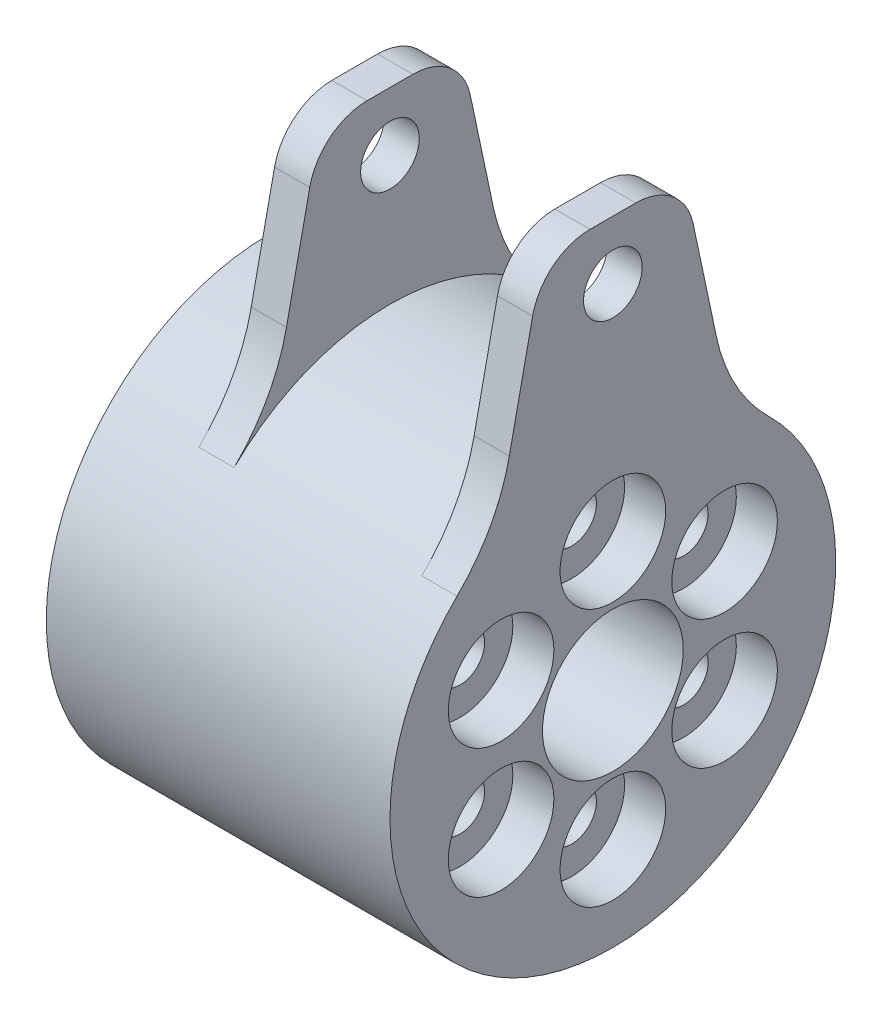
SolidWorks part; units mm, degrees
material "1023 碳钢板 (SS)"
ref_plane "前视基准面" through (0, 0, 0) normal (0, 0, 1) x (1, 0, 0)
ref_plane "上视基准面" through (0, 0, 0) normal (0, 1, 0) x (1, 0, 0)
ref_plane "右视基准面" through (0, 0, 0) normal (1, 0, 0) x (0, 0, -1)
sketch "草图1" plane through (0, 0, 0) normal (1, 0, 0) x (0, 0, -1)
  circle A0 centre (0, 0) radius 19
  circle A1 centre (0, -15) radius 2
  circle A2 centre (0, 13.5) radius 2
  circle A3 centre (11.6913, -6.75) radius 2
  circle A4 centre (-12.9904, 7.5) radius 2
  circle A5 centre (-11.6913, -6.75) radius 2
  circle A6 centre (12.9904, 7.5) radius 2
  circle A7 centre (0, 0) radius 11
  point P17 (0, 0)
  dimension "D1" = 38
  dimension "D2" = 4
  dimension "D3" = 4
  dimension "D4" = 13.5
  dimension "D5" = 15
  dimension "D7" = 22
  dimension "D6" = 3
extrude "凸台-拉伸1" add sketch "草图1" along normal blind 3
sketch "草图3" plane through (3, 0, 0) normal (1, 0, 0) x (0, 0, -1)
  arc A0 (-2.7954, 10.6389) -> (2.7954, 10.6389) centre (0, 13.5) ccw
  circle A1 centre (0, 0) radius 11 construction
  arc A2 (2.7954, 10.6389) -> (-2.7954, 10.6389) centre (0, 0) ccw
  arc A3 (10.6112, -2.8986) -> (7.8159, -7.7403) centre (11.6913, -6.75) ccw
  arc A4 (7.8159, -7.7403) -> (10.6112, -2.8986) centre (0, 0) ccw
  arc A5 (-7.8159, -7.7403) -> (-10.6112, -2.8986) centre (-11.6913, -6.75) ccw
  arc A6 (-10.6112, -2.8986) -> (-7.8159, -7.7403) centre (0, 0) ccw
  circle A7 centre (0, 13.5) radius 2 construction
  point P14 (0, 0)
  dimension "D1" = 8
  dimension "D2" = 3
extrude "凸台-拉伸2" add sketch "草图3" against normal up to surface (3 mm away) up to face at (0, 0, -19)
fillet "圆角1" radius 3 6 edges at (1.5, 10.6389, -2.7954) (1.5, 10.6389, 2.7954) (1.5, -7.7403, -7.8159) (1.5, -2.8986, -10.6112) (1.5, -2.8986, 10.6112) (1.5, -7.7403, 7.8159)
sketch "草图5" plane through (3, 0, 0) normal (1, 0, 0) x (0, 0, -1)
  line L0 (0, 0) -> (0, 54.073) construction
  line L1 (-6, 35) -> (-10, 16.1555)
  line L2 (6, 35) -> (10, 16.1555)
  line L3 (-6, 35) -> (6, 35)
  circle A0 centre (0, 30) radius 2.5
  circle A2 centre (0, 0) radius 19 construction
  arc A3 (10, 16.1555) -> (-10, 16.1555) centre (0, 0) ccw
  dimension "D1" = 30
  dimension "D2" = 5
  dimension "D3" = 5
  dimension "D4" = 20
  dimension "D5" = 12
extrude "凸台-拉伸3" add sketch "草图5" against normal up to surface (3 mm away) up to face at (0, 0, -19)
fillet "圆角2" radius 16 2 edges at (1.5, 16.1555, -10) (1.5, 16.1555, 10)
fillet "圆角3" radius 5 2 edges at (1.5, 35, -6) (1.5, 35, 6)
chamfer "倒角1" [suppressed] distance 2 angle 45
sketch "草图6" [suppressed] plane through (0, 0, 0) normal (-1, 0, 0) x (0, 0, 1)
  circle A0 centre (0, -15) radius 4
  circle A1 centre (0, -15) radius 5
  circle A2 centre (-12.9904, 7.5) radius 4
  circle A3 centre (-12.9904, 7.5) radius 5
  circle A4 centre (12.9904, 7.5) radius 4
  circle A5 centre (12.9904, 7.5) radius 5
  point P13 (0, 0)
  dimension "D1" = 8
  dimension "D2" = 10
  dimension "D3" = 3
extrude "凸台-拉伸4" [suppressed] add sketch "草图6" against normal up to surface (3 mm away)
sketch "草图7" [suppressed] plane through (0, 0, 0) normal (-1, 0, 0) x (0, 0, 1)
  circle A0 centre (0, -15) radius 4
  dimension "D1" = 8
sketch "草图8" plane through (0, 0, 0) normal (-1, 0, 0) x (0, 0, 1)
  arc A0 (9.5574, -3.3668) -> (10.9407, -1.1404) centre (7.9569, -0.8294) ccw construction
  arc A1 (9.5574, -3.3668) -> (7.6944, -6.5935) centre (11.6913, -6.75) ccw construction
  arc A2 (6.458, -8.9048) -> (7.6944, -6.5935) centre (4.6967, -6.4762) ccw construction
  arc A3 (-6.458, -8.9048) -> (6.458, -8.9048) centre (0, 0) ccw construction
  arc A4 (-7.6944, -6.5935) -> (-6.458, -8.9048) centre (-4.6967, -6.4762) ccw construction
  arc A5 (-7.6944, -6.5935) -> (-9.5574, -3.3668) centre (-11.6913, -6.75) ccw construction
  arc A6 (-10.9407, -1.1404) -> (-9.5574, -3.3668) centre (-7.9569, -0.8294) ccw construction
  arc A7 (10.9407, -1.1404) -> (4.4828, 10.0451) centre (0, 0) ccw construction
  arc A8 (4.4828, 10.0451) -> (1.863, 9.9603) centre (3.2602, 7.3056) ccw construction
  arc A9 (-1.863, 9.9603) -> (1.863, 9.9603) centre (0, 13.5) ccw construction
  arc A10 (-1.863, 9.9603) -> (-4.4828, 10.0451) centre (-3.2602, 7.3056) ccw construction
  arc A11 (-4.4828, 10.0451) -> (-10.9407, -1.1404) centre (0, 0) ccw construction
  arc A12 (9.5574, -3.3668) -> (10.9407, -1.1404) centre (7.9569, -0.8294) ccw
  arc A13 (9.5574, -3.3668) -> (7.6944, -6.5935) centre (11.6913, -6.75) ccw
  arc A14 (6.458, -8.9048) -> (7.6944, -6.5935) centre (4.6967, -6.4762) ccw
  arc A15 (-6.458, -8.9048) -> (6.458, -8.9048) centre (0, 0) ccw
  arc A16 (-7.6944, -6.5935) -> (-6.458, -8.9048) centre (-4.6967, -6.4762) ccw
  arc A17 (-7.6944, -6.5935) -> (-9.5574, -3.3668) centre (-11.6913, -6.75) ccw
  arc A18 (-10.9407, -1.1404) -> (-9.5574, -3.3668) centre (-7.9569, -0.8294) ccw
  arc A19 (10.9407, -1.1404) -> (4.4828, 10.0451) centre (0, 0) ccw
  arc A20 (4.4828, 10.0451) -> (1.863, 9.9603) centre (3.2602, 7.3056) ccw
  arc A21 (-1.863, 9.9603) -> (1.863, 9.9603) centre (0, 13.5) ccw
  arc A22 (-1.863, 9.9603) -> (-4.4828, 10.0451) centre (-3.2602, 7.3056) ccw
  arc A23 (-4.4828, 10.0451) -> (-10.9407, -1.1404) centre (0, 0) ccw
  circle A24 centre (0, 0) radius 19
  circle A25 centre (0, -15) radius 2 construction
  circle A26 centre (-11.6913, -6.75) radius 2 construction
  circle A27 centre (11.6913, -6.75) radius 2 construction
  circle A28 centre (12.9904, 7.5) radius 2 construction
  circle A29 centre (0, 13.5) radius 2 construction
  circle A30 centre (-12.9904, 7.5) radius 2 construction
  circle A31 centre (0, -15) radius 2
  circle A32 centre (-11.6913, -6.75) radius 2
  circle A33 centre (11.6913, -6.75) radius 2
  circle A34 centre (12.9904, 7.5) radius 2
  circle A35 centre (0, 13.5) radius 2
  circle A36 centre (-12.9904, 7.5) radius 2
extrude "凸台-拉伸5" add sketch "草图8" along normal blind 8
sketch "草图9" plane through (3, 0, 0) normal (1, 0, 0) x (0, 0, -1)
  line L3 (8.8237, 21.6973) -> (6.8409, 31.0382)
  line L4 (1.9499, 35) -> (-1.9499, 35)
  line L5 (-6.8409, 31.0382) -> (-8.8237, 21.6973)
  line L6 (8.8237, 21.6973) -> (6.8409, 31.0382)
  line L7 (1.9499, 35) -> (-1.9499, 35)
  line L8 (-6.8409, 31.0382) -> (-8.8237, 21.6973)
  circle A0 centre (0, -15) radius 2 construction
  circle A1 centre (11.6913, -6.75) radius 2 construction
  circle A2 centre (-11.6913, -6.75) radius 2 construction
  arc A3 (6.458, -8.9048) -> (7.6944, -6.5935) centre (4.6967, -6.4762) ccw construction
  arc A4 (-6.458, -8.9048) -> (6.458, -8.9048) centre (0, 0) ccw construction
  arc A5 (6.8409, 31.0382) -> (1.9499, 35) centre (1.9499, 30) ccw
  arc A6 (-1.9499, 35) -> (-6.8409, 31.0382) centre (-1.9499, 30) ccw
  arc A7 (-13.2864, 13.582) -> (-8.8237, 21.6973) centre (-24.475, 25.0195) ccw
  arc A8 (-13.2864, 13.582) -> (13.2864, 13.582) centre (0, 0) ccw
  arc A9 (8.8237, 21.6973) -> (13.2864, 13.582) centre (24.475, 25.0195) ccw
  arc A10 (6.8409, 31.0382) -> (1.9499, 35) centre (1.9499, 30) ccw
  arc A11 (-1.9499, 35) -> (-6.8409, 31.0382) centre (-1.9499, 30) ccw
  arc A12 (-13.2864, 13.582) -> (-8.8237, 21.6973) centre (-24.475, 25.0195) ccw
  arc A13 (-13.2864, 13.582) -> (13.2864, 13.582) centre (0, 0) ccw
  arc A14 (8.8237, 21.6973) -> (13.2864, 13.582) centre (24.475, 25.0195) ccw
  arc A15 (-7.6944, -6.5935) -> (-6.458, -8.9048) centre (-4.6967, -6.4762) ccw construction
  arc A16 (9.5574, -3.3668) -> (7.6944, -6.5935) centre (11.6913, -6.75) ccw construction
  arc A17 (9.5574, -3.3668) -> (10.9407, -1.1404) centre (7.9569, -0.8294) ccw construction
  arc A18 (-7.6944, -6.5935) -> (-9.5574, -3.3668) centre (-11.6913, -6.75) ccw construction
  arc A19 (-10.9407, -1.1404) -> (-9.5574, -3.3668) centre (-7.9569, -0.8294) ccw construction
  arc A20 (10.9407, -1.1404) -> (4.4828, 10.0451) centre (0, 0) ccw construction
  arc A21 (-4.4828, 10.0451) -> (-10.9407, -1.1404) centre (0, 0) ccw construction
  arc A22 (4.4828, 10.0451) -> (1.863, 9.9603) centre (3.2602, 7.3056) ccw construction
  arc A23 (-1.863, 9.9603) -> (1.863, 9.9603) centre (0, 13.5) ccw construction
  arc A24 (-1.863, 9.9603) -> (-4.4828, 10.0451) centre (-3.2602, 7.3056) ccw construction
  circle A25 centre (12.9904, 7.5) radius 2 construction
  circle A26 centre (-12.9904, 7.5) radius 2 construction
  circle A27 centre (0, 13.5) radius 2 construction
  circle A28 centre (0, 30) radius 2.5 construction
  circle A29 centre (0, -15) radius 2
  circle A30 centre (11.6913, -6.75) radius 2
  circle A31 centre (-11.6913, -6.75) radius 2
  arc A32 (6.458, -8.9048) -> (7.6944, -6.5935) centre (4.6967, -6.4762) ccw
  arc A33 (-6.458, -8.9048) -> (6.458, -8.9048) centre (0, 0) ccw
  arc A34 (-7.6944, -6.5935) -> (-6.458, -8.9048) centre (-4.6967, -6.4762) ccw
  arc A35 (9.5574, -3.3668) -> (7.6944, -6.5935) centre (11.6913, -6.75) ccw
  arc A36 (9.5574, -3.3668) -> (10.9407, -1.1404) centre (7.9569, -0.8294) ccw
  arc A37 (-7.6944, -6.5935) -> (-9.5574, -3.3668) centre (-11.6913, -6.75) ccw
  arc A38 (-10.9407, -1.1404) -> (-9.5574, -3.3668) centre (-7.9569, -0.8294) ccw
  arc A39 (10.9407, -1.1404) -> (4.4828, 10.0451) centre (0, 0) ccw
  arc A40 (-4.4828, 10.0451) -> (-10.9407, -1.1404) centre (0, 0) ccw
  arc A41 (4.4828, 10.0451) -> (1.863, 9.9603) centre (3.2602, 7.3056) ccw
  arc A42 (-1.863, 9.9603) -> (1.863, 9.9603) centre (0, 13.5) ccw
  arc A43 (-1.863, 9.9603) -> (-4.4828, 10.0451) centre (-3.2602, 7.3056) ccw
  circle A44 centre (12.9904, 7.5) radius 2
  circle A45 centre (-12.9904, 7.5) radius 2
  circle A46 centre (0, 13.5) radius 2
  circle A47 centre (0, 30) radius 2.5
  dimension "D1" = 0
extrude "凸台-拉伸6" add sketch "草图9" along normal blind 25
ref_plane "基准面1" through (6, 0, 0) normal (-1, 0, 0) x (0, 0, 1)
sketch "草图11" plane through (6, 0, 0) normal (-1, 0, 0) x (0, 0, 1)
  line L3 (-6.8409, 31.0382) -> (-8.8237, 21.6973)
  line L4 (1.9499, 35) -> (-1.9499, 35)
  line L5 (8.8237, 21.6973) -> (6.8409, 31.0382)
  line L6 (-6.8409, 31.0382) -> (-8.8237, 21.6973)
  line L7 (1.9499, 35) -> (-1.9499, 35)
  line L8 (8.8237, 21.6973) -> (6.8409, 31.0382)
  arc A0 (13.2864, 13.582) -> (-13.2864, 13.582) centre (0, 0) ccw
  arc A5 (-13.2864, 13.582) -> (-8.8237, 21.6973) centre (-24.475, 25.0195) ccw
  arc A6 (-1.9499, 35) -> (-6.8409, 31.0382) centre (-1.9499, 30) ccw
  arc A7 (6.8409, 31.0382) -> (1.9499, 35) centre (1.9499, 30) ccw
  arc A8 (8.8237, 21.6973) -> (13.2864, 13.582) centre (24.475, 25.0195) ccw
  arc A9 (-13.2864, 13.582) -> (13.2864, 13.582) centre (0, 0) ccw
  arc A10 (-13.2864, 13.582) -> (-8.8237, 21.6973) centre (-24.475, 25.0195) ccw
  arc A11 (-1.9499, 35) -> (-6.8409, 31.0382) centre (-1.9499, 30) ccw
  arc A12 (6.8409, 31.0382) -> (1.9499, 35) centre (1.9499, 30) ccw
  arc A13 (8.8237, 21.6973) -> (13.2864, 13.582) centre (24.475, 25.0195) ccw
  dimension "D1" = 0
extrude "切除-拉伸1" cut sketch "草图11" against normal blind 16 from offset 1.5 offset against normal yes
sketch "草图12" plane through (28, 0, 0) normal (1, 0, 0) x (0, 0, -1)
  circle A0 centre (0, 0) radius 11
  circle A1 centre (0, 0) radius 19
extrude "凸台-拉伸7" add sketch "草图12" against normal blind 36
sketch "草图13" plane through (28, 0, 0) normal (1, 0, 0) x (0, 0, -1)
  line L0 (0, 30) -> (0, -27.4941) construction
  arc A0 (-10.3647, 3.6842) -> (-10.3647, -3.6842) centre (0, 0) ccw
  arc A2 (-1.9917, 10.8182) -> (1.9917, 10.8182) centre (0, 11) ccw
  arc A3 (8.373, 7.134) -> (10.3647, 3.6842) centre (9.5263, 5.5) ccw
  arc A4 (10.3647, -3.6842) -> (8.373, -7.134) centre (9.5263, -5.5) ccw
  arc A5 (1.9917, -10.8182) -> (-1.9917, -10.8182) centre (0, -11) ccw
  arc A6 (-8.373, -7.134) -> (-10.3647, -3.6842) centre (-9.5263, -5.5) ccw
  arc A7 (-10.3647, 3.6842) -> (-8.373, 7.134) centre (-9.5263, 5.5) ccw
  circle A8 centre (0, 0) radius 6
  arc A9 (-1.9917, 10.8182) -> (-8.373, 7.134) centre (0, 0) ccw
  arc A10 (8.373, 7.134) -> (1.9917, 10.8182) centre (0, 0) ccw
  arc A11 (10.3647, -3.6842) -> (10.3647, 3.6842) centre (0, 0) ccw
  arc A12 (1.9917, -10.8182) -> (8.373, -7.134) centre (0, 0) ccw
  arc A13 (-8.373, -7.134) -> (-1.9917, -10.8182) centre (0, 0) ccw
  point P21 (0, 0)
  dimension "D1" = 6
  dimension "D2" = 11
  dimension "D3" = 2
extrude "凸台-拉伸8" add sketch "草图13" against normal blind 36
sketch "草图14" plane through (28, 0, 0) normal (1, 0, 0) x (0, 0, -1)
  circle A0 centre (0, 11) radius 2
  circle A1 centre (-9.5263, 5.5) radius 2
  arc A2 (-8.373, 7.134) -> (-10.3647, 3.6842) centre (0, 0) ccw construction
  circle A3 centre (-9.5263, -5.5) radius 2
  circle A4 centre (0, -11) radius 2
  circle A5 centre (9.5263, -5.5) radius 2
  circle A6 centre (9.5263, 5.5) radius 2
  dimension "D1" = 4
  dimension "D2" = 4
  dimension "D3" = 4
  dimension "D4" = 4
  dimension "D5" = 4
  dimension "D6" = 4
extrude "切除-拉伸2" cut sketch "草图14" against normal blind 36
sketch "草图15" plane through (-8, 0, 0) normal (-1, 0, 0) x (0, 0, 1)
  circle A0 centre (0, 0) radius 28.7129
extrude "切除-拉伸3" cut sketch "草图15" against normal blind 6.7
sketch "草图17" plane through (-1.3, 0, 0) normal (-1, 0, 0) x (0, 0, 1)
  circle A0 centre (-5.5, -9.5263) radius 2
  circle A1 centre (-5.5, 9.5263) radius 1.5
  circle A2 centre (5.5, 9.5263) radius 2
  circle A3 centre (5.5, -9.5263) radius 1.5
extrude "凸台-拉伸9" add sketch "草图17" along normal blind 3.8
chamfer "倒角2" distance 0.5 angle 45 4 edges at (-5.1, -9.5263, -3.5) (-5.1, -9.5263, 7) (-5.1, 9.5263, -4) (-5.1, 9.5263, 7.5)
sketch "草图18" plane through (28, 0, 0) normal (1, 0, 0) x (0, 0, -1)
sketch "草图19" plane through (0, 0, 0) normal (-1, 0, 0) x (0, 0, 1)
  line L3 (8.8237, 21.6973) -> (6.8409, 31.0382)
  line L4 (1.9499, 35) -> (-1.9499, 35)
  line L5 (-6.8409, 31.0382) -> (-8.8237, 21.6973)
  line L6 (8.8237, 21.6973) -> (6.8409, 31.0382)
  line L7 (1.9499, 35) -> (-1.9499, 35)
  line L8 (-6.8409, 31.0382) -> (-8.8237, 21.6973)
  arc A5 (13.2864, 13.582) -> (-13.2864, 13.582) centre (0, 0) ccw
  arc A6 (8.8237, 21.6973) -> (13.2864, 13.582) centre (24.475, 25.0195) ccw
  arc A7 (6.8409, 31.0382) -> (1.9499, 35) centre (1.9499, 30) ccw
  arc A8 (-1.9499, 35) -> (-6.8409, 31.0382) centre (-1.9499, 30) ccw
  arc A9 (-13.2864, 13.582) -> (-8.8237, 21.6973) centre (-24.475, 25.0195) ccw
  arc A10 (13.2864, 13.582) -> (-13.2864, 13.582) centre (0, 0) ccw
  arc A11 (8.8237, 21.6973) -> (13.2864, 13.582) centre (24.475, 25.0195) ccw
  arc A12 (6.8409, 31.0382) -> (1.9499, 35) centre (1.9499, 30) ccw
  arc A13 (-1.9499, 35) -> (-6.8409, 31.0382) centre (-1.9499, 30) ccw
  arc A14 (-13.2864, 13.582) -> (-8.8237, 21.6973) centre (-24.475, 25.0195) ccw
  dimension "D1" = 0
extrude "切除-拉伸4" cut sketch "草图19" against normal blind 3
hole_wizard "M5 螺纹孔的螺纹孔钻头3" positions "草图22" profile "草图23" hole size "M5" standard "GB" end condition through all
sketch "草图22" plane through (28, 0, 0) normal (1, 0, 0) x (0, 0, -1)
  point P0 (0, 11)
  point P3 (9.5263, 5.5)
  point P6 (9.5263, -5.5)
  point P9 (0, -11)
  point P12 (-9.5263, -5.5)
  point P15 (-9.5263, 5.5)
sketch "草图23" plane through (28, 11, 0) normal (0, 1, 0) x (0, 0, -1)
  line L0 (0, 0) -> (0, 33.1)
  line L1 (0, 33.1) -> (2.1, 33.1)
  line L2 (2.1, 33.1) -> (2.1, 0.025)
  line L3 (2.1, 0.025) -> (2.125, 0)
  line L5 (2.125, 0) -> (0, 0)
  line L6 (-2.1, 0.025) -> (-2.125, 0) construction
  line L11 (0, -6.35) -> (0, 107.95) construction
  dimension "通孔孔直径" = 4.2
  dimension "通孔孔深度" = 33.1
  dimension "近端锥形沉头孔直径" = 4.25
  dimension "近端锥形沉头孔角度" = 90
sketch "草图24" plane through (28, 0, 0) normal (1, 0, 0) x (0, 0, -1)
  circle A0 centre (0, 11) radius 4.5
  circle A1 centre (9.5263, 5.5) radius 4.5
  circle A2 centre (9.5263, -5.5) radius 4.5
  circle A3 centre (0, -11) radius 4.5
  circle A4 centre (-9.5263, -5.5) radius 4.5
  circle A5 centre (-9.5263, 5.5) radius 4.5
  dimension "D1" = 9
  dimension "D2" = 9
  dimension "D3" = 9
  dimension "D4" = 9
  dimension "D5" = 9
  dimension "D6" = 9
extrude "切除-拉伸5" cut sketch "草图24" against normal blind 3.5
sketch "草图25" plane through (23.5, 0, 0) normal (-1, 0, 0) x (0, 0, 1)
  line L3 (8.8237, 21.6973) -> (6.8409, 31.0382)
  line L4 (1.9499, 35) -> (-1.9499, 35)
  line L5 (-6.8409, 31.0382) -> (-8.8237, 21.6973)
  line L6 (8.8237, 21.6973) -> (6.8409, 31.0382)
  line L7 (1.9499, 35) -> (-1.9499, 35)
  line L8 (-6.8409, 31.0382) -> (-8.8237, 21.6973)
  arc A5 (-13.2864, 13.582) -> (-8.8237, 21.6973) centre (-24.475, 25.0195) ccw
  arc A6 (13.2864, 13.582) -> (-13.2864, 13.582) centre (0, 0) ccw
  arc A7 (8.8237, 21.6973) -> (13.2864, 13.582) centre (24.475, 25.0195) ccw
  arc A8 (6.8409, 31.0382) -> (1.9499, 35) centre (1.9499, 30) ccw
  arc A9 (-1.9499, 35) -> (-6.8409, 31.0382) centre (-1.9499, 30) ccw
  arc A10 (-13.2864, 13.582) -> (-8.8237, 21.6973) centre (-24.475, 25.0195) ccw
  arc A11 (13.2864, 13.582) -> (-13.2864, 13.582) centre (0, 0) ccw
  arc A12 (8.8237, 21.6973) -> (13.2864, 13.582) centre (24.475, 25.0195) ccw
  arc A13 (6.8409, 31.0382) -> (1.9499, 35) centre (1.9499, 30) ccw
  arc A14 (-1.9499, 35) -> (-6.8409, 31.0382) centre (-1.9499, 30) ccw
  dimension "D1" = 0
extrude "切除-拉伸6" cut sketch "草图25" against normal blind 1.5
sketch "草图26" plane through (3, 0, 0) normal (-1, 0, 0) x (0, 0, 1)
  line L3 (8.8237, 21.6973) -> (6.8409, 31.0382)
  line L4 (1.9499, 35) -> (-1.9499, 35)
  line L5 (-6.8409, 31.0382) -> (-8.8237, 21.6973)
  line L6 (8.8237, 21.6973) -> (6.8409, 31.0382)
  line L7 (1.9499, 35) -> (-1.9499, 35)
  line L8 (-6.8409, 31.0382) -> (-8.8237, 21.6973)
  arc A5 (8.8237, 21.6973) -> (13.2864, 13.582) centre (24.475, 25.0195) ccw
  arc A6 (6.8409, 31.0382) -> (1.9499, 35) centre (1.9499, 30) ccw
  arc A7 (-1.9499, 35) -> (-6.8409, 31.0382) centre (-1.9499, 30) ccw
  arc A8 (-13.2864, 13.582) -> (-8.8237, 21.6973) centre (-24.475, 25.0195) ccw
  arc A9 (13.2864, 13.582) -> (-13.2864, 13.582) centre (0, 0) ccw
  arc A10 (8.8237, 21.6973) -> (13.2864, 13.582) centre (24.475, 25.0195) ccw
  arc A11 (6.8409, 31.0382) -> (1.9499, 35) centre (1.9499, 30) ccw
  arc A12 (-1.9499, 35) -> (-6.8409, 31.0382) centre (-1.9499, 30) ccw
  arc A13 (-13.2864, 13.582) -> (-8.8237, 21.6973) centre (-24.475, 25.0195) ccw
  arc A14 (13.2864, 13.582) -> (-13.2864, 13.582) centre (0, 0) ccw
  dimension "D1" = 0
extrude "切除-拉伸7" cut sketch "草图26" against normal blind 1.5
sketch "草图28" plane through (7.5, 0, 0) normal (1, 0, 0) x (0, 0, -1)
  line L3 (8.8237, 21.6973) -> (6.8409, 31.0382)
  line L4 (1.9499, 35) -> (-1.9499, 35)
  line L5 (-6.8409, 31.0382) -> (-8.8237, 21.6973)
  line L6 (8.8237, 21.6973) -> (6.8409, 31.0382)
  line L7 (1.9499, 35) -> (-1.9499, 35)
  line L8 (-6.8409, 31.0382) -> (-8.8237, 21.6973)
  circle A0 centre (0, 30) radius 2.5 construction
  circle A1 centre (0, 30) radius 2.5
  arc A5 (8.8237, 21.6973) -> (13.2864, 13.582) centre (24.475, 25.0195) ccw
  arc A6 (6.8409, 31.0382) -> (1.9499, 35) centre (1.9499, 30) ccw
  arc A7 (-1.9499, 35) -> (-6.8409, 31.0382) centre (-1.9499, 30) ccw
  arc A8 (-13.2864, 13.582) -> (-8.8237, 21.6973) centre (-24.475, 25.0195) ccw
  arc A9 (13.2864, 13.582) -> (-13.2864, 13.582) centre (0, 0) ccw
  arc A10 (8.8237, 21.6973) -> (13.2864, 13.582) centre (24.475, 25.0195) ccw
  arc A11 (6.8409, 31.0382) -> (1.9499, 35) centre (1.9499, 30) ccw
  arc A12 (-1.9499, 35) -> (-6.8409, 31.0382) centre (-1.9499, 30) ccw
  arc A13 (-13.2864, 13.582) -> (-8.8237, 21.6973) centre (-24.475, 25.0195) ccw
  arc A14 (13.2864, 13.582) -> (-13.2864, 13.582) centre (0, 0) ccw
  dimension "D1" = 0
extrude "凸台-拉伸10" add sketch "草图28" along normal blind 1.5
sketch "草图29" plane through (4.5, 0, 0) normal (-1, 0, 0) x (0, 0, 1)
  line L3 (8.8237, 21.6973) -> (6.8409, 31.0382)
  line L4 (1.9499, 35) -> (-1.9499, 35)
  line L5 (-6.8409, 31.0382) -> (-8.8237, 21.6973)
  line L6 (8.8237, 21.6973) -> (6.8409, 31.0382)
  line L7 (1.9499, 35) -> (-1.9499, 35)
  line L8 (-6.8409, 31.0382) -> (-8.8237, 21.6973)
  arc A5 (8.8237, 21.6973) -> (13.2864, 13.582) centre (24.475, 25.0195) ccw
  arc A6 (6.8409, 31.0382) -> (1.9499, 35) centre (1.9499, 30) ccw
  arc A7 (-1.9499, 35) -> (-6.8409, 31.0382) centre (-1.9499, 30) ccw
  arc A8 (-13.2864, 13.582) -> (-8.8237, 21.6973) centre (-24.475, 25.0195) ccw
  arc A9 (13.2864, 13.582) -> (-13.2864, 13.582) centre (0, 0) ccw
  arc A10 (8.8237, 21.6973) -> (13.2864, 13.582) centre (24.475, 25.0195) ccw
  arc A11 (6.8409, 31.0382) -> (1.9499, 35) centre (1.9499, 30) ccw
  arc A12 (-1.9499, 35) -> (-6.8409, 31.0382) centre (-1.9499, 30) ccw
  arc A13 (-13.2864, 13.582) -> (-8.8237, 21.6973) centre (-24.475, 25.0195) ccw
  arc A14 (13.2864, 13.582) -> (-13.2864, 13.582) centre (0, 0) ccw
  dimension "D1" = 0
extrude "切除-拉伸8" cut sketch "草图29" against normal blind 1.5
move or copy body "实体-移动/复制6" [suppressed] bodies to move or copy 113
move or copy body "实体-移动/复制7" [suppressed] bodies to move or copy 118
move or copy body "实体-移动/复制5" [suppressed] bodies to move or copy 113
move or copy body "实体-移动/复制4" [suppressed] bodies to move or copy 118
move or copy body "实体-移动/复制3" [suppressed] bodies to move or copy 113
move or copy body "实体-移动/复制2" [suppressed] bodies to move or copy 113
move or copy body "实体-移动/复制1" [suppressed] bodies to move or copy 109
